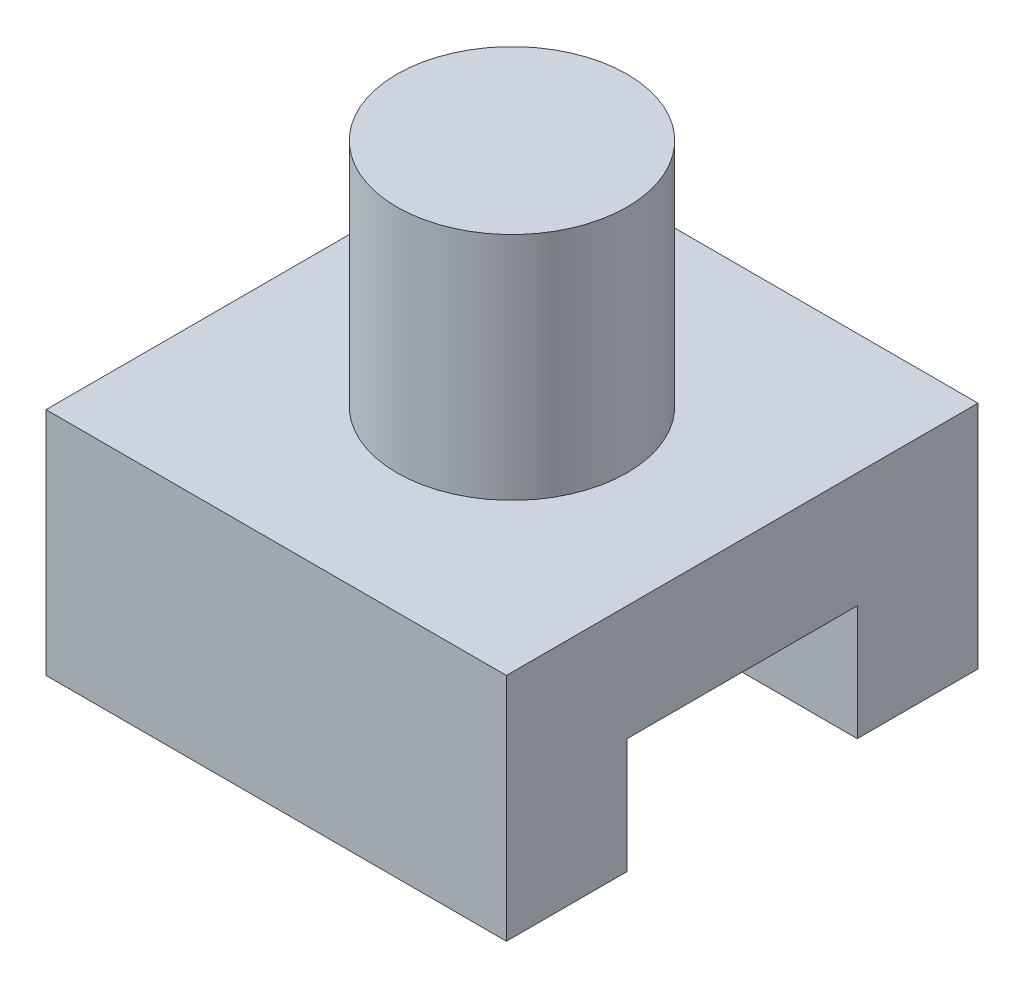
SolidWorks part; units mm, degrees
ref_plane "Front Plane" through (0, 0, 0) normal (0, 0, 1) x (1, 0, 0)
ref_plane "Top Plane" through (0, 0, 0) normal (0, 1, 0) x (1, 0, 0)
ref_plane "Right Plane" through (0, 0, 0) normal (1, 0, 0) x (0, 0, -1)
sketch "Sketch1" plane through (0, 0, 0) normal (1, 0, 0) x (0, 0, -1)
  line L0 (-25.4, 0) -> (-25.4, -25.4)
  line L1 (-52.039, -25.4) -> (-25.4, -25.4)
  line L2 (-52.039, -25.4) -> (-52.039, 25.4)
  line L3 (-52.039, 25.4) -> (52.039, 25.4)
  line L4 (52.039, -25.4) -> (52.039, 25.4)
  line L5 (-52.039, -25.4) -> (52.039, 25.4) construction
  line L6 (-52.039, 25.4) -> (52.039, -25.4) construction
  line L7 (-25.4, 0) -> (25.4, 0)
  line L9 (25.4, 0) -> (25.4, -25.4)
  line L10 (-25.4, 0) -> (25.4, -25.4) construction
  line L11 (-25.4, -25.4) -> (25.4, 0) construction
  line L12 (25.4, -25.4) -> (52.039, -25.4)
  point P0 (0, 0)
  point P7 (0, -12.7)
  dimension "D1" = 50.8
  dimension "D2" = 104.078
  dimension "D3" = 50.8
  dimension "D4" = 25.4
extrude "Boss-Extrude1" add sketch "Sketch1" along normal blind 101.6
sketch "Sketch2" plane through (0, 25.4, 0) normal (0, 1, 0) x (1, 0, 0)
  line L0 (50.8, 52.039) -> (50.8, -55.8275) construction
  line L1 (101.6, 52.039) -> (0, 52.039) construction
  line L2 (0, 0) -> (101.6, 0) construction
  line L3 (0, 52.039) -> (0, -52.039) construction
  line L4 (101.6, 52.039) -> (101.6, -52.039) construction
  circle A0 centre (50.8, 0) radius 25.4
  dimension "D1" = 50.8
extrude "Boss-Extrude2" add sketch "Sketch2" along normal blind 50.8
